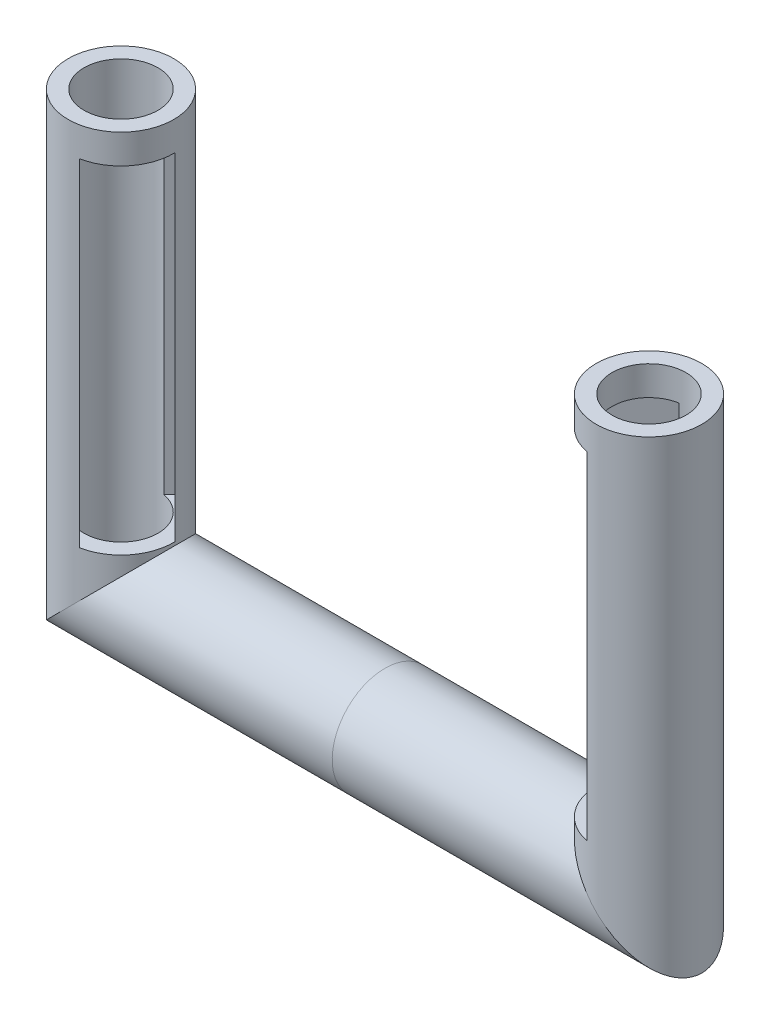
SolidWorks part; units mm, degrees
ref_plane "Front Plane" through (0, 0, 0) normal (0, 0, 1) x (1, 0, 0)
ref_plane "Top Plane" through (0, 0, 0) normal (0, 1, 0) x (1, 0, 0)
ref_plane "Right Plane" through (0, 0, 0) normal (1, 0, 0) x (0, 0, -1)
sketch "Sketch1" plane through (0, 0, 0) normal (0, 0, 1) x (1, 0, 0)
  line L0 (25, 0) -> (-25, 0) construction
  line L1 (0, 40) -> (0, -40) construction
  line L2 (0, -40) -> (-25, -40)
  line L3 (-25, -40) -> (-25, 0)
  line L4 (25, 0) -> (25, -40)
  line L5 (25, -40) -> (0, -40)
  point P3 (0, 0)
  point P4 (0, 0)
  point P9 (0, 0)
sweep "Sweep1" add path "Sketch1" circular profile diameter 10 parameters "D3"=10
sketch "Sketch17" plane through (0, 0, 0) normal (0, 1, 0) x (1, 0, 0)
  circle A0 centre (-25, 0) radius 3.5
  circle A1 centre (25, 0) radius 3.5
extrude "Cut-Extrude1" cut sketch "Sketch17" against normal through all
ref_plane "Plane1" through (-8.9645, 0, -8.9645) normal (0.7071, 0, 0.7071) x (0, 1, 0)
sketch "Sketch18" plane through (-8.9645, 0, -8.9645) normal (0.7071, 0, 0.7071) x (0, 1, 0)
  line L1 (-34.6836, 14.0528) -> (-2.7786, 14.0528)
  line L2 (-34.6836, 14.0528) -> (-34.6836, 20.4472)
  line L3 (-34.6836, 20.4472) -> (-2.7786, 20.4472)
  line L4 (-2.7786, 14.0528) -> (-2.7786, 20.4472)
  line L5 (-34.6836, 14.0528) -> (-2.7786, 20.4472) construction
  line L6 (-34.6836, 20.4472) -> (-2.7786, 14.0528) construction
  point P0 (-18.7311, 17.25)
  point P5 (-34.6836, 20.4472)
extrude "Cut-Extrude2" cut sketch "Sketch18" against normal blind 7
ref_plane "Plane2" through (8.9645, 0, -8.9645) normal (-0.7071, 0, 0.7071) x (0.7071, 0, 0.7071)
mirror "Mirror1" about plane through (-8.9645, 0, -8.9645) normal (0.7071, 0, 0.7071) of "Cut-Extrude2" second plane through (0, 0, 0) second plane normal (1, 0, 0)
